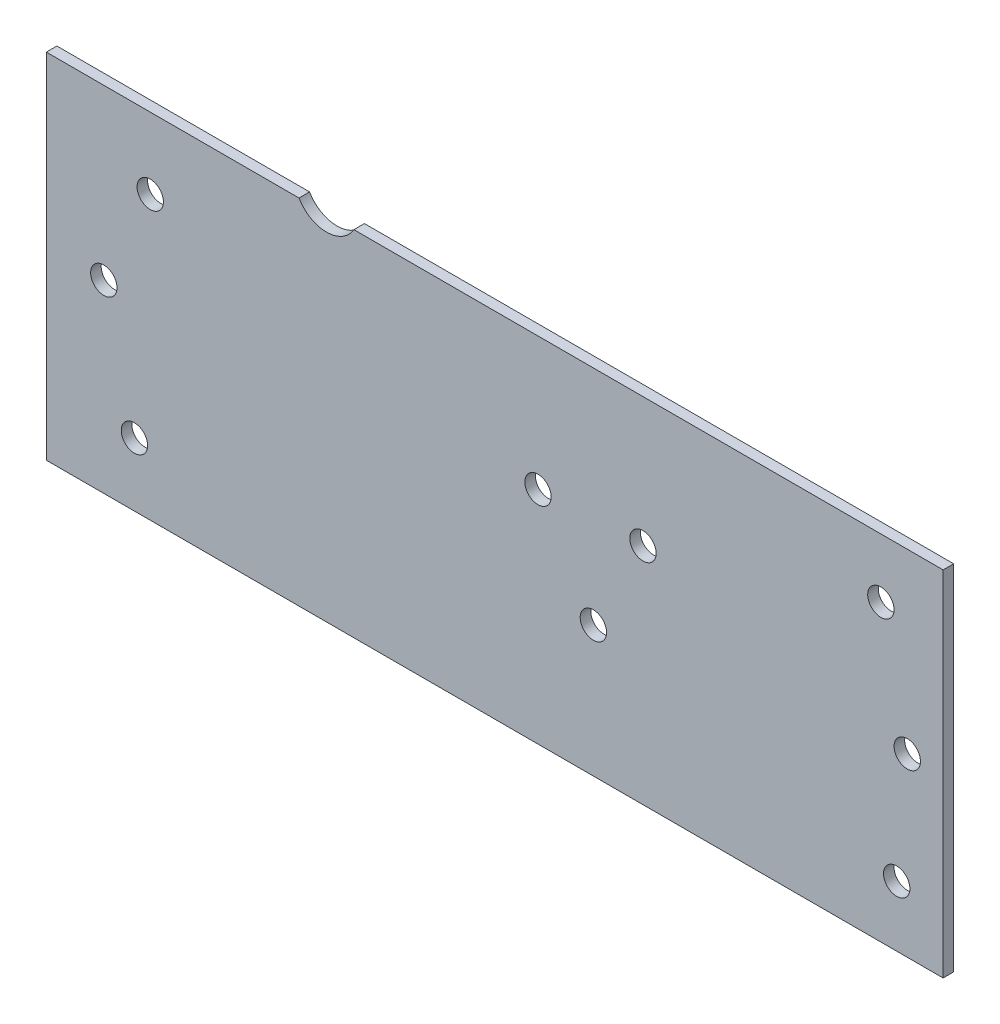
SolidWorks part; units mm, degrees
ref_plane "Front Plane" through (0, 0, 0) normal (0, 0, 1) x (1, 0, 0)
ref_plane "Top Plane" through (0, 0, 0) normal (0, 1, 0) x (1, 0, 0)
ref_plane "Right Plane" through (0, 0, 0) normal (1, 0, 0) x (0, 0, -1)
sketch "Sketch1" plane through (0, 0, 0) normal (0, 0, 1) x (1, 0, 0)
  line L1 (91, -33.5) -> (-88.5, -33.5) construction
  line L2 (-85, -33.5) -> (85, -33.5)
  line L3 (-85, -33.5) -> (-85, 33.5)
  line L4 (-85, 33.5) -> (85, 33.5)
  line L5 (85, -33.5) -> (85, 33.5)
  line L7 (-26.7038, 33.5) -> (88, 33.5) construction
  circle A0 centre (8.2, 8.3) radius 2.5
  circle A1 centre (28.1, 9) radius 2.5
  circle A2 centre (18.7, -8.7) radius 2.5
  circle A3 centre (73.2, 22.3) radius 2.5
  circle A4 centre (78.2, -0.1) radius 2.5
  circle A5 centre (76.2, -22) radius 2.5
  circle A6 centre (-68.3, -21.5) radius 2.5
  circle A7 centre (-74.1, 1.5) radius 2.5
  circle A8 centre (-65.3, 20) radius 2.5
  circle A16 centre (28.1, 9) radius 2.5 construction
  circle A17 centre (-31.9, 36.5) radius 6
  arc A18 (-37.0962, 33.5) -> (-26.7038, 33.5) centre (-31.9, 36.5) ccw construction
  circle A19 centre (-68.3, -21.5) radius 2.5 construction
  circle A20 centre (8.2, 8.3) radius 2.5 construction
  circle A21 centre (18.7, -8.7) radius 2.5 construction
  circle A22 centre (76.2, -22) radius 2.5 construction
  circle A23 centre (78.2, -0.1) radius 2.5 construction
  circle A24 centre (73.2, 22.3) radius 2.5 construction
  circle A25 centre (-65.3, 20) radius 2.5 construction
  circle A26 centre (-74.1, 1.5) radius 2.5 construction
  point P44 (0, 33.5)
  dimension "D1" = 170
extrude "Boss-Extrude1" add sketch "Sketch1" along normal blind 2
